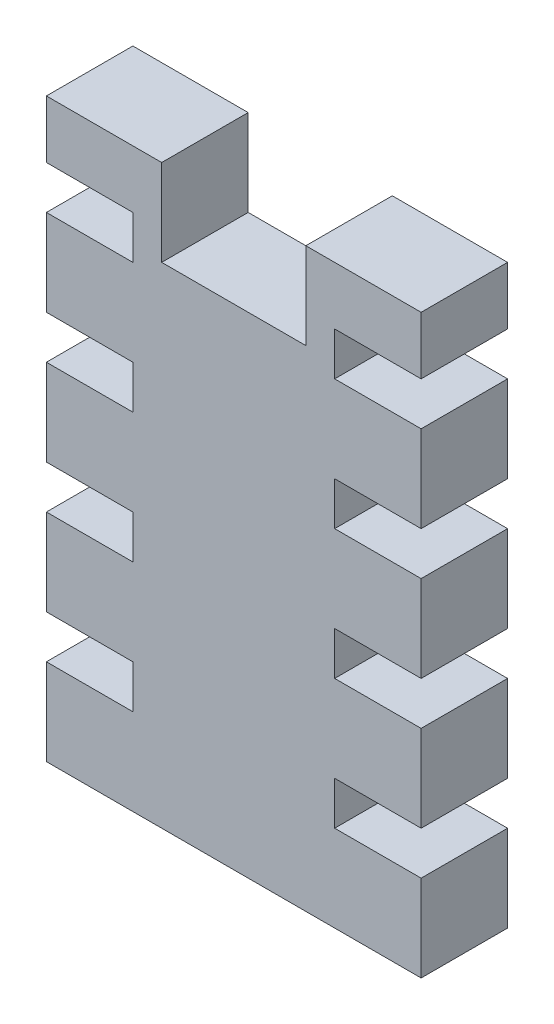
SolidWorks part; units mm, degrees
ref_plane "Plan de face" through (0, 0, 0) normal (0, 0, 1) x (1, 0, 0)
ref_plane "Plan de dessus" through (0, 0, 0) normal (0, 1, 0) x (1, 0, 0)
ref_plane "Plan de droite" through (0, 0, 0) normal (1, 0, 0) x (0, 0, -1)
sketch "Sketch1" plane through (0, 0, 0) normal (0, 0, 1) x (1, 0, 0)
  line L1 (6.5, -5.3665) -> (-6.5, -5.3665)
  line L2 (6.5, -5.3665) -> (6.5, 14.6335)
  line L3 (6.5, 14.6335) -> (-6.5, 14.6335)
  line L4 (-6.5, -5.3665) -> (-6.5, 14.6335)
  line L5 (6.5, -5.3665) -> (-6.5, 14.6335) construction
  line L6 (6.5, 14.6335) -> (-6.5, -5.3665) construction
  point P0 (0, 4.6335)
  dimension "D1" = 13
  dimension "D2" = 20
extrude "Boss-Extrude1" add sketch "Sketch1" along normal blind 3
sketch "Sketch2" plane through (0, 0, 3) normal (0, 0, 1) x (1, 0, 0)
  line L0 (-6.5, 14.6335) -> (-6.5, -5.3665) construction
  line L1 (-6.5, 12.6335) -> (-3.5, 12.6335)
  line L2 (-6.5, 12.6335) -> (-6.5, 11.1335)
  line L3 (-6.5, 11.1335) -> (-3.5, 11.1335)
  line L4 (-3.5, 12.6335) -> (-3.5, 11.1335)
  line L5 (6.5, 14.6335) -> (-6.5, 14.6335) construction
  line L7 (-6.5, 8.1335) -> (-3.5, 8.1335)
  line L8 (-6.5, 8.1335) -> (-6.5, 6.6335)
  line L9 (-6.5, 6.6335) -> (-3.5, 6.6335)
  line L10 (-3.5, 8.1335) -> (-3.5, 6.6335)
  dimension "D1" = 2
  dimension "D2" = 3
  dimension "D3" = 1.5
  dimension "D4" = 1.5
  dimension "D5" = 3
  dimension "D6" = 3
extrude "Cut-Extrude1" cut sketch "Sketch2" against normal blind 3
sketch "Sketch3" plane through (0, 0, 3) normal (0, 0, 1) x (1, 0, 0)
  line L0 (6.5, -5.3665) -> (6.5, 14.6335) construction
  line L1 (6.5, 12.6335) -> (3.5, 12.6335)
  line L2 (6.5, 12.6335) -> (6.5, 11.1335)
  line L3 (6.5, 11.1335) -> (3.5, 11.1335)
  line L4 (3.5, 12.6335) -> (3.5, 11.1335)
  line L5 (6.5, 14.6335) -> (-6.5, 14.6335) construction
  line L7 (6.5, 8.1335) -> (3.5, 8.1335)
  line L8 (6.5, 8.1335) -> (6.5, 6.6335)
  line L9 (6.5, 6.6335) -> (3.5, 6.6335)
  line L10 (3.5, 8.1335) -> (3.5, 6.6335)
  dimension "D1" = 3
  dimension "D2" = 1.5
  dimension "D3" = 2
  dimension "D4" = 3
  dimension "D5" = 1.5
  dimension "D6" = 3
extrude "Cut-Extrude2" cut sketch "Sketch3" against normal blind 3
sketch "Sketch5" plane through (0, 0, 3) normal (0, 0, 1) x (1, 0, 0)
  line L0 (6.5, 14.6335) -> (-6.5, 14.6335) construction
  line L1 (-2.5, 14.6335) -> (2.5, 14.6335)
  line L2 (-2.5, 14.6335) -> (-2.5, 11.6335)
  line L3 (-2.5, 11.6335) -> (2.5, 11.6335)
  line L4 (2.5, 14.6335) -> (2.5, 11.6335)
  line L5 (-6.5, 14.6335) -> (-6.5, 12.6335) construction
  dimension "D1" = 4
  dimension "D2" = 5
  dimension "D3" = 3
extrude "Cut-Extrude6" cut sketch "Sketch5" against normal blind 3
sketch "Sketch6" plane through (0, 0, 3) normal (0, 0, 1) x (1, 0, 0)
  line L0 (-6.5, 6.6335) -> (-6.5, -5.3665) construction
  line L1 (-6.5, 3.6335) -> (-3.5, 3.6335)
  line L2 (-6.5, 3.6335) -> (-6.5, 2.1335)
  line L3 (-6.5, 2.1335) -> (-3.5, 2.1335)
  line L4 (-3.5, 3.6335) -> (-3.5, 2.1335)
  line L5 (-6.5, 6.6335) -> (-3.5, 6.6335) construction
  line L7 (-6.5, -0.8665) -> (-3.5, -0.8665)
  line L8 (-6.5, -0.8665) -> (-6.5, -2.3665)
  line L9 (-6.5, -2.3665) -> (-3.5, -2.3665)
  line L10 (-3.5, -0.8665) -> (-3.5, -2.3665)
  line L13 (6.5, -5.3665) -> (6.5, 6.6335) construction
  line L14 (6.5, 3.6335) -> (3.5, 3.6335)
  line L15 (6.5, 3.6335) -> (6.5, 2.1335)
  line L16 (6.5, 2.1335) -> (3.5, 2.1335)
  line L17 (3.5, 3.6335) -> (3.5, 2.1335)
  line L19 (3.5, -0.8665) -> (6.5, -0.8665)
  line L20 (3.5, -0.8665) -> (3.5, -2.3665)
  line L21 (3.5, -2.3665) -> (6.5, -2.3665)
  line L22 (6.5, -0.8665) -> (6.5, -2.3665)
  dimension "D1" = 3
  dimension "D2" = 1.5
  dimension "D3" = 3
  dimension "D4" = 1.5
  dimension "D5" = 3
  dimension "D6" = 3
  dimension "D7" = 3
extrude "Cut-Extrude7" cut sketch "Sketch6" against normal blind 10
